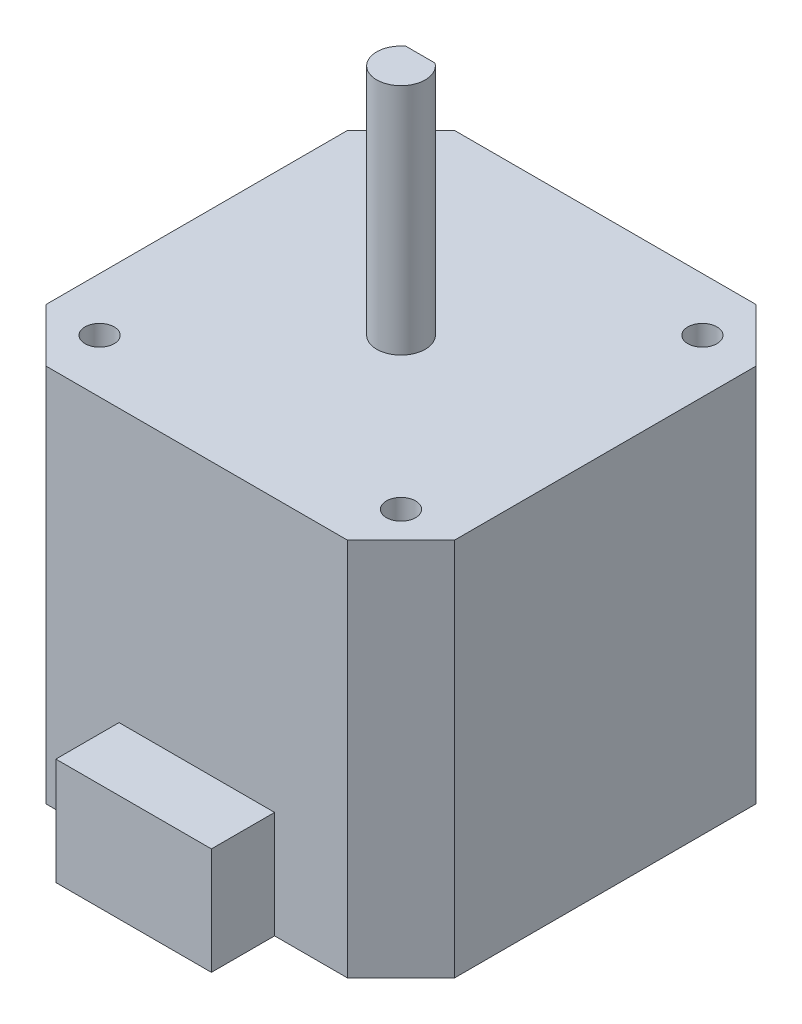
SolidWorks part; units mm, degrees
ref_plane "Front Plane" through (0, 0, 0) normal (0, 0, 1) x (1, 0, 0)
ref_plane "Top Plane" through (0, 0, 0) normal (0, 1, 0) x (1, 0, 0)
ref_plane "Right Plane" through (0, 0, 0) normal (1, 0, 0) x (0, 0, -1)
sketch "Sketch1" plane through (0, 0, 0) normal (0, 1, 0) x (1, 0, 0)
  line L0 (-21, 15.5) -> (-15.5, 21)
  line L1 (15.5, 21) -> (21, 15.5)
  line L2 (-15.5, -21) -> (15.5, -21)
  line L3 (-21, -15.5) -> (-21, 15.5)
  line L4 (-15.5, 21) -> (15.5, 21)
  line L5 (21, -15.5) -> (21, 15.5)
  line L6 (-21, -15.5) -> (-15.5, -21)
  line L7 (15.5, -21) -> (21, -15.5)
  line L8 (-21, 15.5) -> (21, 15.5) construction
  dimension "D1" = 21
  dimension "D2" = 42
  dimension "D3" = 31
  dimension "D4" = 21
  dimension "D5" = 42
  dimension "D6" = 45
extrude "Boss-Extrude1" add sketch "Sketch1" along normal blind 39
sketch "Sketch2" plane through (0, 39, 0) normal (0, 1, 0) x (1, 0, 0)
  circle A0 centre (0, 0) radius 2.5
  dimension "D1" = 5
extrude "Boss-Extrude2" add sketch "Sketch2" along normal blind 9
sketch "Sketch3" plane through (0, 48, 0) normal (0, 1, 0) x (1, 0, 0)
  line L0 (-1.5, 2) -> (1.5, 2)
  line L1 (0, 0) -> (0, -2.5) construction
  arc A0 (-1.5, 2) -> (1.5, 2) centre (0, 0) ccw
  dimension "D2" = 2.5
  dimension "D1" = 4.5
extrude "Boss-Extrude3" add sketch "Sketch3" along normal blind 15
sketch "Sketch4" plane through (0, 39, 0) normal (0, 1, 0) x (1, 0, 0)
  circle A0 centre (-15.5, 15.5) radius 1.5
  circle A1 centre (15.5, 15.5) radius 1.5
  circle A2 centre (15.5, -15.5) radius 1.5
  circle A3 centre (-15.5, -15.5) radius 1.5
  dimension "D1" = 3
extrude "Cut-Extrude1" cut sketch "Sketch4" against normal blind 4.5
sketch "Sketch5" plane through (0, 0, 21) normal (0, 0, 1) x (1, 0, 0)
  line L0 (-15.5, 0) -> (15.5, 0) construction
  line L1 (-8, 0) -> (8, 0)
  line L2 (-8, 0) -> (-8, 11)
  line L3 (-8, 11) -> (8, 11)
  line L4 (8, 0) -> (8, 11)
  dimension "D1" = 11
  dimension "D2" = 16
  dimension "D3" = 8
extrude "Boss-Extrude4" add sketch "Sketch5" along normal blind 6.5
